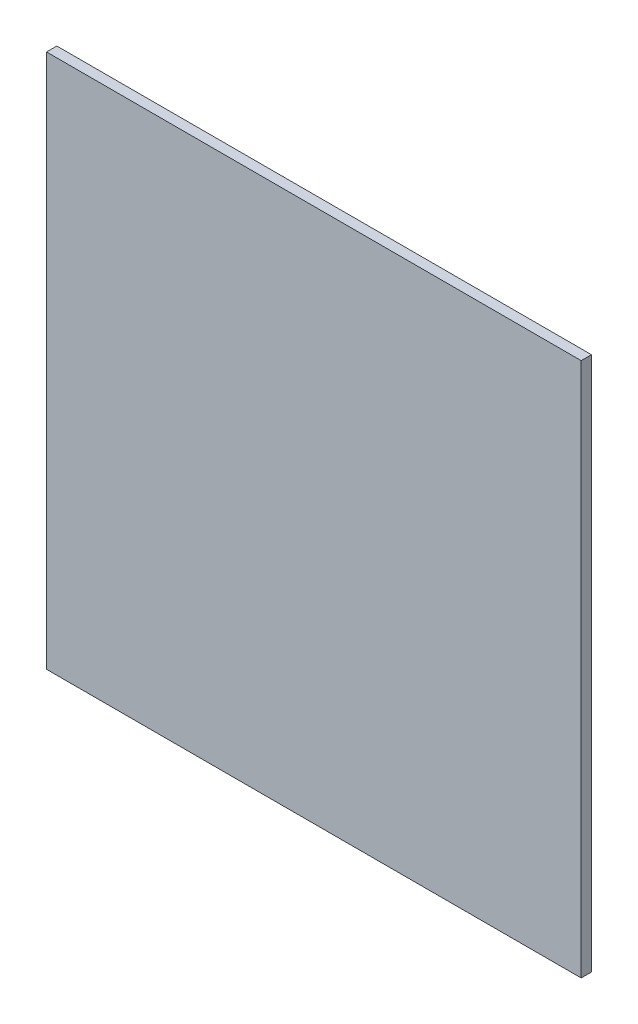
SolidWorks part; units mm, degrees
ref_plane "Front" through (0, 0, 0) normal (0, 0, 1) x (1, 0, 0)
ref_plane "Top" through (0, 0, 0) normal (0, 1, 0) x (1, 0, 0)
ref_plane "Right" through (0, 0, 0) normal (1, 0, 0) x (0, 0, -1)
sketch "Sketch1" plane through (0, 0, 0) normal (0, 0, 1) x (1, 0, 0)
  line L1 (0, 0) -> (520, 0)
  line L2 (0, 0) -> (0, 520)
  line L3 (0, 520) -> (520, 520)
  line L4 (520, 0) -> (520, 520)
  dimension "D1" = 520
  dimension "D2" = 520
extrude "Boss-Extrude1" add sketch "Sketch1" along normal blind 10
